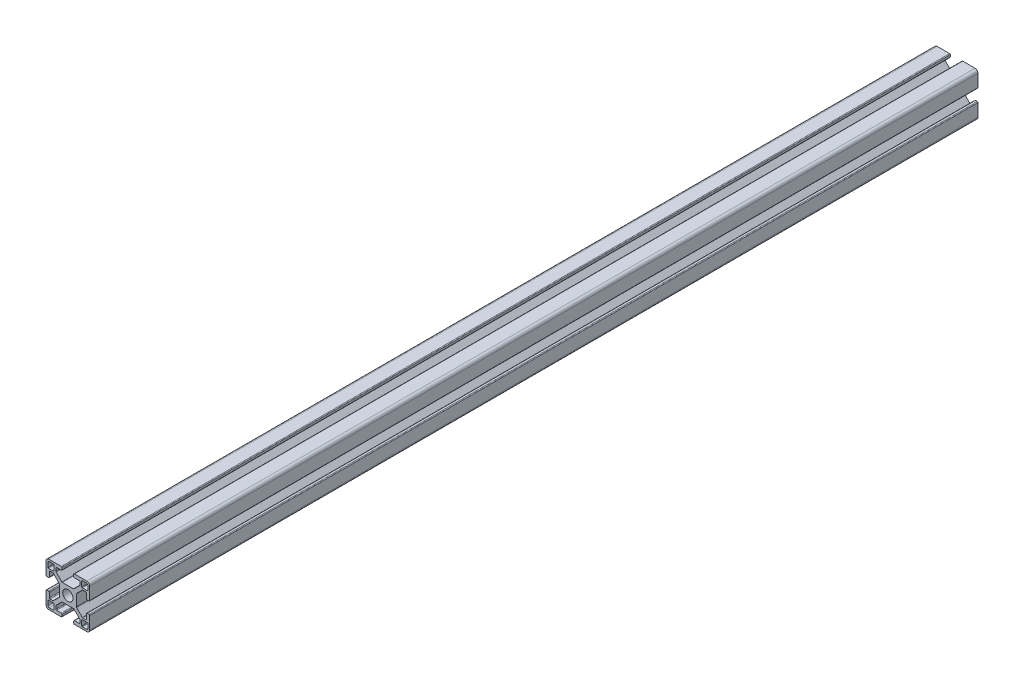
SolidWorks part; units mm, degrees
ref_plane "Front Plane" through (0, 0, 0) normal (0, 0, 1) x (1, 0, 0)
ref_plane "Top Plane" through (0, 0, 0) normal (0, 1, 0) x (1, 0, 0)
ref_plane "Right Plane" through (0, 0, 0) normal (1, 0, 0) x (0, 0, -1)
sketch "Sketch1" plane through (0, 0, 0) normal (0, 0, 1) x (1, 0, 0)
  line L0 (3.9799, -2.4733) -> (3.1981, -1.4942) construction
  line L1 (1.4942, -3.1981) -> (2.4733, -3.9799) construction
  line L2 (-2.4733, -3.9799) -> (-1.4942, -3.1981) construction
  line L3 (-3.1981, -1.4942) -> (-3.9799, -2.4733) construction
  line L4 (-3.9799, 2.4733) -> (-3.1981, 1.4942) construction
  line L5 (-1.4942, 3.1981) -> (-2.4733, 3.9799) construction
  line L6 (2.4733, 3.9799) -> (1.4942, 3.1981) construction
  line L7 (3.1981, 1.4942) -> (3.9799, 2.4733) construction
  line L8 (-12.6999, -13.6999) -> (-9.881, -13.6999)
  line L9 (-13.6999, -9.881) -> (-13.6999, -12.6999)
  line L10 (-9.88, -9.5) -> (-13.3189, -9.5)
  line L11 (-9.5, -13.3189) -> (-9.5, -9.88)
  line L12 (13.6999, -12.6999) -> (13.6999, -9.881)
  line L13 (9.881, -13.6999) -> (12.6999, -13.6999)
  line L14 (9.5, -9.88) -> (9.5, -13.3189)
  line L15 (13.3189, -9.5) -> (9.88, -9.5)
  line L16 (9.88, 9.5) -> (13.3189, 9.5)
  line L17 (9.5, 13.3189) -> (9.5, 9.88)
  line L18 (12.6999, 13.6999) -> (9.881, 13.6999)
  line L19 (13.6999, 9.881) -> (13.6999, 12.6999)
  line L20 (-13.6999, 12.6999) -> (-13.6999, 9.881)
  line L21 (-9.881, 13.6999) -> (-12.6999, 13.6999)
  line L22 (-9.5, 9.88) -> (-9.5, 13.3189)
  line L23 (-13.3189, 9.5) -> (-9.88, 9.5)
  line L24 (14.4999, -4) -> (13.2425, -4)
  line L25 (12.7425, -4.5) -> (12.7425, -7.7325)
  line L26 (12.2428, -8.25) -> (10.2602, -8.25)
  line L27 (9.9066, -8.1035) -> (5.9811, -4.178)
  line L28 (5.8347, -3.8245) -> (5.8347, -1.0125)
  line L29 (5.8347, -1.0125) -> (5.3247, -0.0625) construction
  line L30 (5.3247, -0.0625) -> (5.8347, 0.8875) construction
  line L31 (5.8347, 0.8875) -> (5.8347, 3.8245)
  line L32 (5.9811, 4.178) -> (9.9066, 8.1035)
  line L33 (10.2602, 8.25) -> (12.2428, 8.25)
  line L34 (12.7425, 7.7325) -> (12.7425, 4.5)
  line L35 (13.2425, 4) -> (14.4999, 4)
  line L36 (14.9999, 4.5) -> (14.9999, 12.9999)
  line L37 (12.9999, 14.9999) -> (4.5, 14.9999)
  line L38 (4, 14.4999) -> (4, 13.2425)
  line L39 (4.5, 12.7425) -> (7.7325, 12.7425)
  line L40 (8.25, 12.2428) -> (8.25, 10.2602)
  line L41 (8.1035, 9.9066) -> (4.178, 5.9811)
  line L42 (3.8245, 5.8347) -> (0.95, 5.8347)
  line L43 (0.95, 5.8347) -> (0, 5.3247) construction
  line L44 (0, 5.3247) -> (-0.95, 5.8347) construction
  line L45 (-0.95, 5.8347) -> (-3.8245, 5.8347)
  line L46 (-4.178, 5.9811) -> (-8.1035, 9.9066)
  line L47 (-8.25, 10.2602) -> (-8.25, 12.2428)
  line L48 (-7.7325, 12.7425) -> (-4.5, 12.7425)
  line L49 (-4, 13.2425) -> (-4, 14.4999)
  line L50 (-4.5, 14.9999) -> (-12.9999, 14.9999)
  line L51 (-14.9999, 12.9999) -> (-14.9999, 4.5)
  line L52 (-14.4999, 4) -> (-13.2425, 4)
  line L53 (-12.7425, 4.5) -> (-12.7425, 7.7325)
  line L54 (-12.2428, 8.25) -> (-10.2602, 8.25)
  line L55 (-9.9066, 8.1035) -> (-5.9811, 4.178)
  line L56 (-5.8347, 3.8245) -> (-5.8347, 0.8875)
  line L57 (-5.8347, 0.8875) -> (-5.3247, -0.0625) construction
  line L58 (-5.3247, -0.0625) -> (-5.8347, -1.0125) construction
  line L59 (-5.8347, -1.0125) -> (-5.8347, -3.8245)
  line L60 (-5.9811, -4.178) -> (-9.9066, -8.1035)
  line L61 (-10.2602, -8.25) -> (-12.2428, -8.25)
  line L62 (-12.7425, -7.7325) -> (-12.7425, -4.5)
  line L63 (-13.2425, -4) -> (-14.4999, -4)
  line L64 (-14.9999, -4.5) -> (-14.9999, -12.9999)
  line L65 (-12.9999, -14.9999) -> (-4.5, -14.9999)
  line L66 (-4, -14.4999) -> (-4, -13.2425)
  line L67 (-4.5, -12.7425) -> (-7.7325, -12.7425)
  line L68 (-8.25, -12.2428) -> (-8.25, -10.2602)
  line L69 (-8.1035, -9.9066) -> (-4.178, -5.9811)
  line L70 (-3.8245, -5.8347) -> (-0.95, -5.8347)
  line L71 (-0.95, -5.8347) -> (0, -5.3247) construction
  line L72 (0, -5.3247) -> (0.95, -5.8347) construction
  line L73 (0.95, -5.8347) -> (3.8245, -5.8347)
  line L74 (4.178, -5.9811) -> (8.1035, -9.9066)
  line L75 (8.25, -10.2602) -> (8.25, -12.2428)
  line L76 (7.7325, -12.7425) -> (4.5, -12.7425)
  line L77 (4, -13.2425) -> (4, -14.4999)
  line L78 (4.5, -14.9999) -> (12.9999, -14.9999)
  line L79 (14.9999, -12.9999) -> (14.9999, -4.5)
  line L80 (-5.8347, -1.0125) -> (-5.8347, 0.8875)
  line L81 (-0.95, 5.8347) -> (0.95, 5.8347)
  line L82 (5.8347, 0.8875) -> (5.8347, -1.0125)
  line L83 (-0.95, -5.8347) -> (0.95, -5.8347)
  arc A0 (2.4733, -3.9799) -> (3.9799, -2.4733) centre (3.1422, -3.1422) ccw construction
  arc A1 (-1.4942, -3.1981) -> (1.4942, -3.1981) centre (0, 0) ccw construction
  arc A2 (-3.9799, -2.4733) -> (-2.4733, -3.9799) centre (-3.1422, -3.1422) ccw construction
  arc A3 (-3.1981, 1.4942) -> (-3.1981, -1.4942) centre (0, 0) ccw construction
  arc A4 (-2.4733, 3.9799) -> (-3.9799, 2.4733) centre (-3.1422, 3.1422) ccw construction
  arc A5 (1.4942, 3.1981) -> (-1.4942, 3.1981) centre (0, 0) ccw construction
  arc A6 (3.9799, 2.4733) -> (2.4733, 3.9799) centre (3.1422, 3.1422) ccw construction
  arc A7 (3.1981, -1.4942) -> (3.1981, 1.4942) centre (0, 0) ccw construction
  arc A8 (-13.6999, -12.6999) -> (-12.6999, -13.6999) centre (-12.6999, -12.6999) ccw
  arc A9 (-13.3189, -9.5) -> (-13.6999, -9.881) centre (-13.3189, -9.881) ccw
  arc A10 (-9.5, -9.88) -> (-9.88, -9.5) centre (-9.88, -9.88) ccw
  arc A11 (-9.881, -13.6999) -> (-9.5, -13.3189) centre (-9.881, -13.3189) ccw
  arc A12 (12.6999, -13.6999) -> (13.6999, -12.6999) centre (12.6999, -12.6999) ccw
  arc A13 (9.5, -13.3189) -> (9.881, -13.6999) centre (9.881, -13.3189) ccw
  arc A14 (9.88, -9.5) -> (9.5, -9.88) centre (9.88, -9.88) ccw
  arc A15 (13.6999, -9.881) -> (13.3189, -9.5) centre (13.3189, -9.881) ccw
  arc A16 (9.5, 9.88) -> (9.88, 9.5) centre (9.88, 9.88) ccw
  arc A17 (9.881, 13.6999) -> (9.5, 13.3189) centre (9.881, 13.3189) ccw
  arc A18 (13.6999, 12.6999) -> (12.6999, 13.6999) centre (12.6999, 12.6999) ccw
  arc A19 (13.3189, 9.5) -> (13.6999, 9.881) centre (13.3189, 9.881) ccw
  arc A20 (14.9999, -4.5) -> (14.4999, -4) centre (14.4999, -4.5) ccw
  arc A21 (13.2425, -4) -> (12.7425, -4.5) centre (13.2425, -4.5) ccw
  arc A22 (12.2428, -8.25) -> (12.7425, -7.7325) centre (12.2428, -7.75) ccw
  arc A23 (9.9066, -8.1035) -> (10.2602, -8.25) centre (10.2602, -7.75) ccw
  arc A24 (5.8347, -3.8245) -> (5.9811, -4.178) centre (6.3347, -3.8245) ccw
  arc A25 (5.9811, 4.178) -> (5.8347, 3.8245) centre (6.3347, 3.8245) ccw
  arc A26 (10.2602, 8.25) -> (9.9066, 8.1035) centre (10.2602, 7.75) ccw
  arc A27 (12.7425, 7.7325) -> (12.2428, 8.25) centre (12.2428, 7.75) ccw
  arc A28 (12.7425, 4.5) -> (13.2425, 4) centre (13.2425, 4.5) ccw
  arc A29 (14.4999, 4) -> (14.9999, 4.5) centre (14.4999, 4.5) ccw
  arc A30 (14.9999, 12.9999) -> (12.9999, 14.9999) centre (12.9999, 12.9999) ccw
  arc A31 (4.5, 14.9999) -> (4, 14.4999) centre (4.5, 14.4999) ccw
  arc A32 (4, 13.2425) -> (4.5, 12.7425) centre (4.5, 13.2425) ccw
  arc A33 (8.25, 12.2428) -> (7.7325, 12.7425) centre (7.75, 12.2428) ccw
  arc A34 (8.1035, 9.9066) -> (8.25, 10.2602) centre (7.75, 10.2602) ccw
  arc A35 (3.8245, 5.8347) -> (4.178, 5.9811) centre (3.8245, 6.3347) ccw
  arc A36 (-4.178, 5.9811) -> (-3.8245, 5.8347) centre (-3.8245, 6.3347) ccw
  arc A37 (-8.25, 10.2602) -> (-8.1035, 9.9066) centre (-7.75, 10.2602) ccw
  arc A38 (-7.7325, 12.7425) -> (-8.25, 12.2428) centre (-7.75, 12.2428) ccw
  arc A39 (-4.5, 12.7425) -> (-4, 13.2425) centre (-4.5, 13.2425) ccw
  arc A40 (-4, 14.4999) -> (-4.5, 14.9999) centre (-4.5, 14.4999) ccw
  arc A41 (-12.9999, 14.9999) -> (-14.9999, 12.9999) centre (-12.9999, 12.9999) ccw
  arc A42 (-14.9999, 4.5) -> (-14.4999, 4) centre (-14.4999, 4.5) ccw
  arc A43 (-13.2425, 4) -> (-12.7425, 4.5) centre (-13.2425, 4.5) ccw
  arc A44 (-12.2428, 8.25) -> (-12.7425, 7.7325) centre (-12.2428, 7.75) ccw
  arc A45 (-9.9066, 8.1035) -> (-10.2602, 8.25) centre (-10.2602, 7.75) ccw
  arc A46 (-5.8347, 3.8245) -> (-5.9811, 4.178) centre (-6.3347, 3.8245) ccw
  arc A47 (-5.9811, -4.178) -> (-5.8347, -3.8245) centre (-6.3347, -3.8245) ccw
  arc A48 (-10.2602, -8.25) -> (-9.9066, -8.1035) centre (-10.2602, -7.75) ccw
  arc A49 (-12.7425, -7.7325) -> (-12.2428, -8.25) centre (-12.2428, -7.75) ccw
  arc A50 (-12.7425, -4.5) -> (-13.2425, -4) centre (-13.2425, -4.5) ccw
  arc A51 (-14.4999, -4) -> (-14.9999, -4.5) centre (-14.4999, -4.5) ccw
  arc A52 (-14.9999, -12.9999) -> (-12.9999, -14.9999) centre (-12.9999, -12.9999) ccw
  arc A53 (-4.5, -14.9999) -> (-4, -14.4999) centre (-4.5, -14.4999) ccw
  arc A54 (-4, -13.2425) -> (-4.5, -12.7425) centre (-4.5, -13.2425) ccw
  arc A55 (-8.25, -12.2428) -> (-7.7325, -12.7425) centre (-7.75, -12.2428) ccw
  arc A56 (-8.1035, -9.9066) -> (-8.25, -10.2602) centre (-7.75, -10.2602) ccw
  arc A57 (-3.8245, -5.8347) -> (-4.178, -5.9811) centre (-3.8245, -6.3347) ccw
  arc A58 (4.178, -5.9811) -> (3.8245, -5.8347) centre (3.8245, -6.3347) ccw
  arc A59 (8.25, -10.2602) -> (8.1035, -9.9066) centre (7.75, -10.2602) ccw
  arc A60 (7.7325, -12.7425) -> (8.25, -12.2428) centre (7.75, -12.2428) ccw
  arc A61 (4.5, -12.7425) -> (4, -13.2425) centre (4.5, -13.2425) ccw
  arc A62 (4, -14.4999) -> (4.5, -14.9999) centre (4.5, -14.4999) ccw
  arc A63 (12.9999, -14.9999) -> (14.9999, -12.9999) centre (12.9999, -12.9999) ccw
  arc A64 (-12.6999, 13.6999) -> (-13.6999, 12.6999) centre (-12.6999, 12.6999) ccw
  arc A65 (-9.5, 13.3189) -> (-9.881, 13.6999) centre (-9.881, 13.3189) ccw
  arc A66 (-9.88, 9.5) -> (-9.5, 9.88) centre (-9.88, 9.88) ccw
  arc A67 (-13.6999, 9.881) -> (-13.3189, 9.5) centre (-13.3189, 9.881) ccw
  circle A68 centre (0, 0) radius 3.53
extrude "Boss-Extrude1" add sketch "Sketch1" along normal mid plane 609.6
